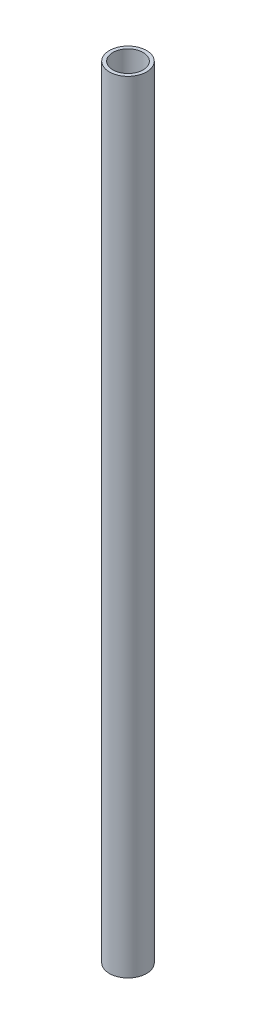
SolidWorks part; units mm, degrees
ref_plane "Front Plane" through (0, 0, 0) normal (0, 0, 1) x (1, 0, 0)
ref_plane "Top Plane" through (0, 0, 0) normal (0, 1, 0) x (1, 0, 0)
ref_plane "Right Plane" through (0, 0, 0) normal (1, 0, 0) x (0, 0, -1)
sketch "Sketch1" plane through (0, 0, 0) normal (0, 1, 0) x (1, 0, 0)
  circle A0 centre (0, 0) radius 3.8735
  circle A1 centre (0, 0) radius 4.7625
extrude "Boss-Extrude1" add sketch "Sketch1" along normal blind 200.0001
